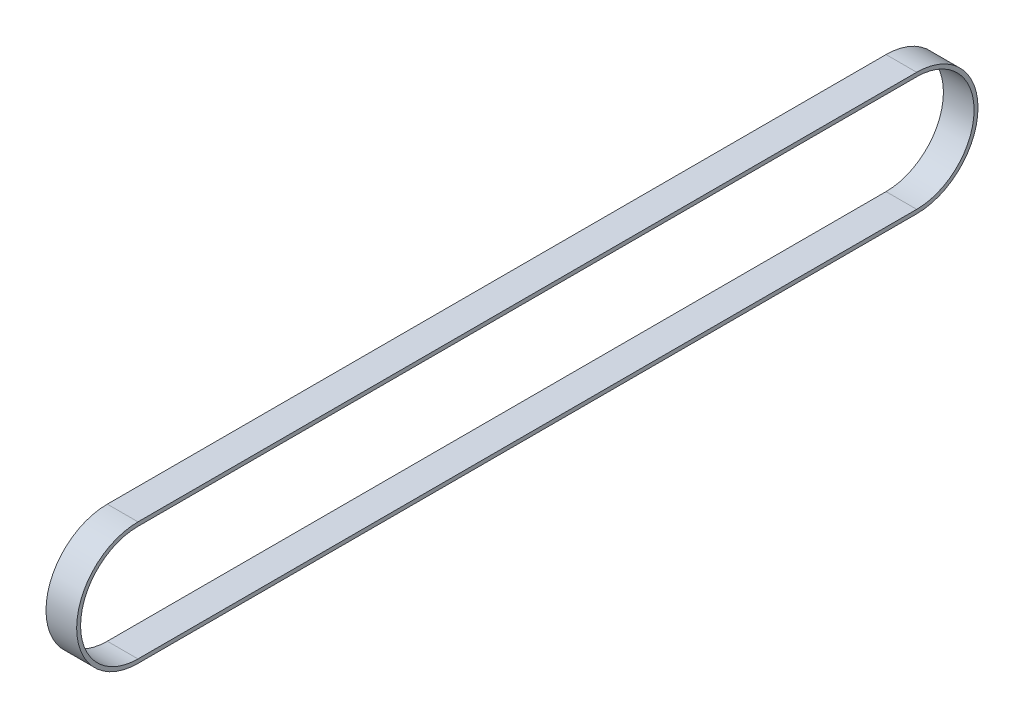
SolidWorks part; units mm, degrees
ref_plane "Front Plane" through (0, 0, 0) normal (0, 0, 1) x (1, 0, 0)
ref_plane "Top Plane" through (0, 0, 0) normal (0, 1, 0) x (1, 0, 0)
ref_plane "Right Plane" through (0, 0, 0) normal (1, 0, 0) x (0, 0, -1)
sketch "Sketch1" plane through (0, 0, 0) normal (1, 0, 0) x (0, 0, -1)
  line L0 (0, 0) -> (381, 0) construction
  line L1 (0, 28.08) -> (381, 28.08)
  line L2 (0, -28.08) -> (381, -28.08)
  line L3 (0, 0) -> (381, 0) construction
  line L4 (0, 30) -> (381, 30)
  line L5 (0, -30) -> (381, -30)
  arc A0 (0, 28.08) -> (0, -28.08) centre (0, 0) ccw
  arc A1 (381, -28.08) -> (381, 28.08) centre (381, 0) ccw
  arc A2 (0, 30) -> (0, -30) centre (0, 0) ccw
  arc A3 (381, -30) -> (381, 30) centre (381, 0) ccw
  point P3 (190.5, 0)
  point P8 (190.5, 0)
  dimension "D2" = 28.08
  dimension "D3" = 30
  dimension "D1" = 381
extrude "Boss-Extrude1" add sketch "Sketch1" along normal blind 15
